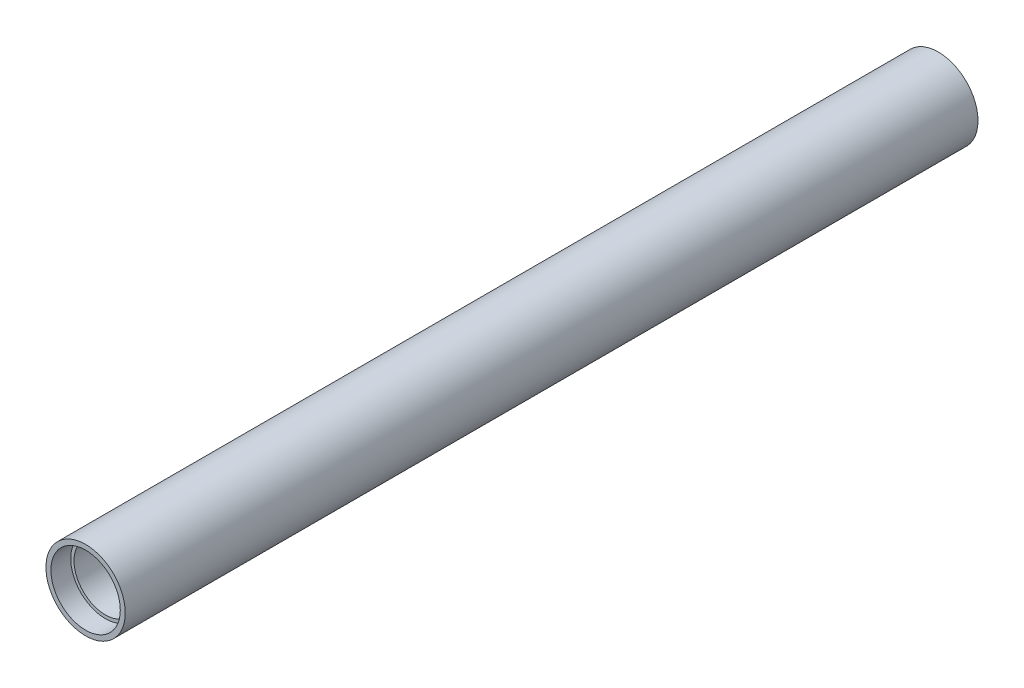
SolidWorks part; units mm, degrees
ref_plane "Ön Düzlem" through (0, 0, 0) normal (0, 0, 1) x (1, 0, 0)
ref_plane "Üst Düzlem" through (0, 0, 0) normal (0, 1, 0) x (1, 0, 0)
ref_plane "Sağ Düzlem" through (0, 0, 0) normal (1, 0, 0) x (0, 0, -1)
sketch "Çizim1" plane through (0, 0, 0) normal (0, 0, 1) x (1, 0, 0)
  circle A0 centre (0, 0) radius 19
  circle A1 centre (0, 0) radius 24
  dimension "D1" = 48
  dimension "D2" = 38
extrude "Yükseklik-Ekstrüzyon1" add sketch "Çizim1" along normal blind 516
sketch "Çizim2" plane through (0, 0, 516) normal (0, 0, 1) x (1, 0, 0)
  circle A0 centre (0, 0) radius 19
  circle A1 centre (0, 0) radius 21
  dimension "D1" = 42
  dimension "D2" = 38
extrude "Kes-Ekstrüzyon1" cut sketch "Çizim2" against normal blind 12
sketch "Çizim3" plane through (0, 0, 0) normal (0, 0, -1) x (-1, 0, 0)
  circle A0 centre (0, 0) radius 19
  circle A1 centre (0, 0) radius 21
  dimension "D1" = 42
  dimension "D2" = 38
extrude "Kes-Ekstrüzyon2" cut sketch "Çizim3" against normal blind 12
